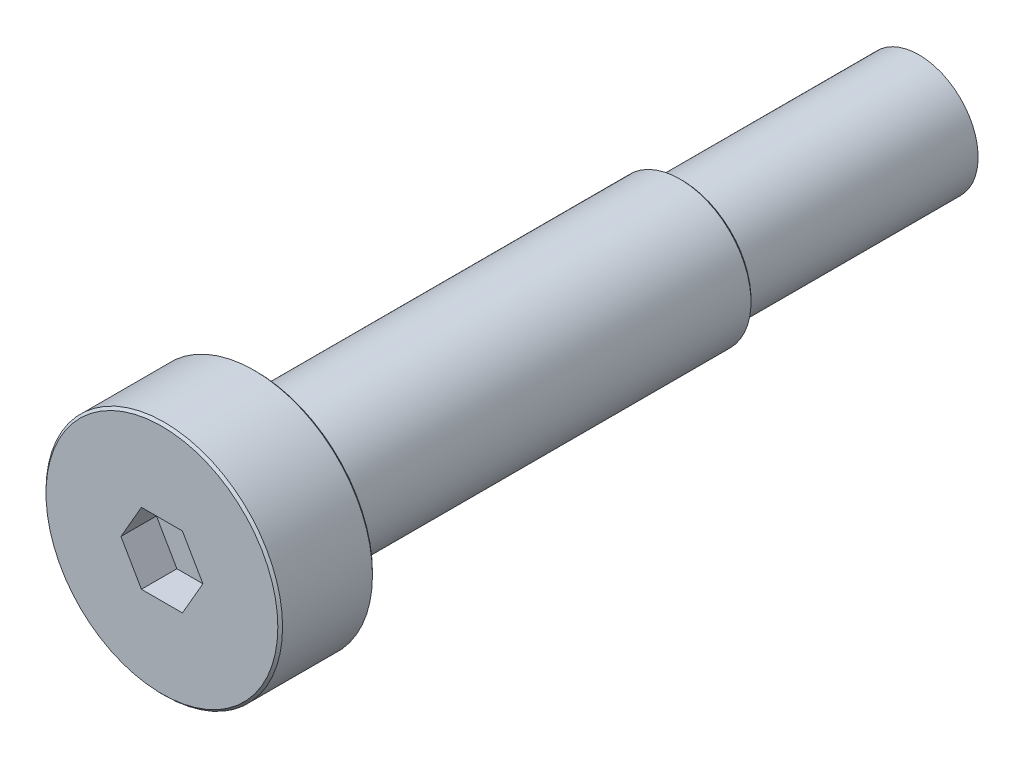
SolidWorks part; units mm, degrees
ref_plane "前视基准面" through (0, 0, 0) normal (0, 0, 1) x (1, 0, 0)
ref_plane "上视基准面" through (0, 0, 0) normal (0, 1, 0) x (1, 0, 0)
ref_plane "右视基准面" through (0, 0, 0) normal (1, 0, 0) x (0, 0, -1)
other "Configuration Table"
sketch "草图1" plane through (0, 0, 0) normal (0, 0, 1) x (1, 0, 0)
  circle A0 centre (0, 0) radius 5
  dimension "D1" = 10
extrude "凸台-拉伸1" add sketch "草图1" against normal blind 4
sketch "草图2" plane through (0, 0, -4) normal (0, 0, -1) x (-1, 0, 0)
  circle A0 centre (0, 0) radius 3
  dimension "D1" = 6
extrude "凸台-拉伸2" add sketch "草图2" along normal blind 18
sketch "草图3" plane through (0, 0, -22) normal (0, 0, -1) x (-1, 0, 0)
  circle A0 centre (0, 0) radius 2.5
  dimension "D1" = 5
extrude "凸台-拉伸3" add sketch "草图3" along normal blind 10
chamfer "倒角1" distance 0.1 angle 45 3 edges at (-3, 0, -22) (5, 0, -4) (5, 0, 0)
sketch "草图4" plane through (0, 0, 0) normal (0, 0, 1) x (1, 0, 0)
  line L1 (1.7321, 0) -> (0.866, 1.5)
  line L2 (0.866, 1.5) -> (-0.866, 1.5)
  line L3 (-0.866, 1.5) -> (-1.7321, 0)
  line L4 (-1.7321, 0) -> (-0.866, -1.5)
  line L5 (-0.866, -1.5) -> (0.866, -1.5)
  line L6 (0.866, -1.5) -> (1.7321, 0)
  circle A0 centre (0, 0) radius 1.5 construction
  point P1 (0, 0)
  dimension "D1" = 3
extrude "切除-拉伸1" cut sketch "草图4" against normal blind 1.5
